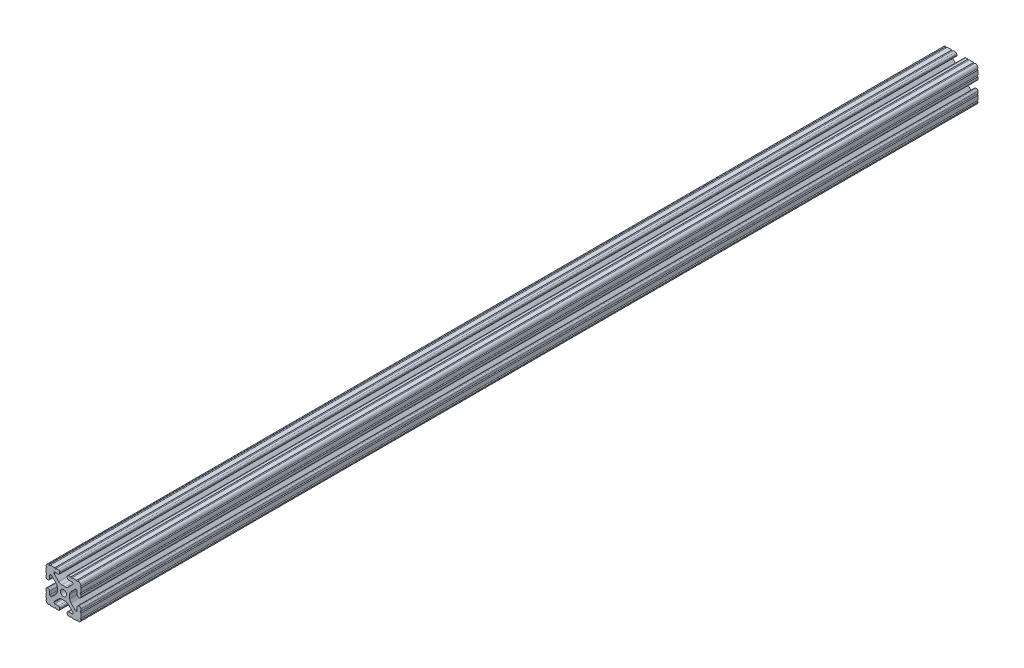
SolidWorks part; units mm, degrees
material "6061 Alloy"
ref_plane "Front Plane" through (0, 0, 0) normal (0, 0, 1) x (1, 0, 0)
ref_plane "Top Plane" through (0, 0, 0) normal (0, 1, 0) x (1, 0, 0)
ref_plane "Right Plane" through (0, 0, 0) normal (1, 0, 0) x (0, 0, -1)
sketch "Sketch1" plane through (0, 0, 0) normal (0, 0, 1) x (1, 0, 0)
  line L0 (0, 25.6181) -> (0, -24.623) construction
  line L1 (-20.8943, 0) -> (20.4607, 0) construction
  line L2 (-10.0229, 12.9148) -> (-5.2522, 8.144)
  line L3 (-10.287, 14.0843) -> (-10.287, 13.5524)
  line L4 (-5.6176, 14.986) -> (-9.3853, 14.986)
  line L5 (-4.064, 17.4964) -> (-4.064, 16.5396)
  line L6 (-7.9742, 19.05) -> (-5.6176, 19.05)
  line L7 (-14.3277, 19.05) -> (-9.4982, 19.05)
  line L8 (-19.05, 9.4961) -> (-19.05, 14.3277)
  line L9 (-19.05, 5.6176) -> (-19.05, 7.9763)
  line L10 (-16.5396, 4.064) -> (-17.4964, 4.064)
  line L11 (-14.986, 9.3853) -> (-14.986, 5.6176)
  line L12 (-13.516, 10.287) -> (-14.0843, 10.287)
  line L13 (-8.1476, 5.2921) -> (-12.8784, 10.0229)
  line L14 (-6.7564, -1.9335) -> (-6.7564, 1.9335)
  line L15 (-12.8784, -10.0229) -> (-8.1476, -5.2921)
  line L16 (-14.0843, -10.287) -> (-13.516, -10.287)
  line L17 (-14.986, -5.6176) -> (-14.986, -9.3853)
  line L18 (-17.4964, -4.064) -> (-16.5396, -4.064)
  line L19 (-19.05, -7.9763) -> (-19.05, -5.6176)
  line L20 (-19.05, -14.3277) -> (-19.05, -9.4961)
  line L21 (-9.4961, -19.05) -> (-14.3277, -19.05)
  line L22 (-5.6176, -19.05) -> (-7.9763, -19.05)
  line L23 (-4.064, -17.4964) -> (-4.064, -16.5396)
  line L24 (10.0229, -12.9148) -> (5.2522, -8.144)
  line L25 (10.287, -14.0843) -> (10.287, -13.5524)
  line L26 (5.6176, -14.986) -> (9.3853, -14.986)
  line L28 (-1.9022, 6.7564) -> (1.9022, 6.7564)
  line L29 (-1.9022, -6.7564) -> (1.9022, -6.7564)
  line L31 (-5.6176, -14.986) -> (-9.3853, -14.986)
  line L32 (-10.287, -14.0843) -> (-10.287, -13.5524)
  line L33 (-10.0229, -12.9148) -> (-5.2522, -8.144)
  line L66 (4.064, -16.5396) -> (4.064, -17.4964)
  line L67 (5.6176, -19.05) -> (7.9763, -19.05)
  line L68 (9.4961, -19.05) -> (14.3277, -19.05)
  line L69 (19.05, -14.3277) -> (19.05, -9.4961)
  line L70 (19.05, -7.9763) -> (19.05, -5.6176)
  line L71 (17.4964, -4.064) -> (16.5396, -4.064)
  line L72 (14.986, -5.6176) -> (14.986, -9.3853)
  line L73 (14.0843, -10.287) -> (13.516, -10.287)
  line L74 (12.8784, -10.0229) -> (8.1476, -5.2921)
  line L75 (6.7564, -1.9335) -> (6.7564, 1.9335)
  line L76 (8.1476, 5.2921) -> (12.8784, 10.0229)
  line L77 (13.516, 10.287) -> (14.0843, 10.287)
  line L78 (14.986, 9.3853) -> (14.986, 5.6176)
  line L79 (16.5396, 4.064) -> (17.4964, 4.064)
  line L80 (19.05, 5.6176) -> (19.05, 7.9763)
  line L81 (19.05, 9.4961) -> (19.05, 14.3277)
  line L82 (14.3277, 19.05) -> (9.4982, 19.05)
  line L83 (7.9742, 19.05) -> (5.6176, 19.05)
  line L84 (4.064, 17.4964) -> (4.064, 16.5396)
  line L85 (5.6176, 14.986) -> (9.3853, 14.986)
  line L86 (10.287, 14.0843) -> (10.287, 13.5524)
  line L87 (10.0229, 12.9148) -> (5.2522, 8.144)
  arc A0 (-10.0229, 12.9148) -> (-10.287, 13.5524) centre (-9.3853, 13.5524) cw
  circle A1 centre (0, 0) radius 3.3274
  arc A2 (-10.287, 14.0843) -> (-9.3853, 14.986) centre (-9.3853, 14.0843) cw
  arc A3 (-4.064, 16.5396) -> (-5.6176, 14.986) centre (-5.6176, 16.5396) cw
  arc A4 (-5.6176, 19.05) -> (-4.064, 17.4964) centre (-5.6176, 17.4964) cw
  arc A5 (-7.9742, 19.05) -> (-9.4982, 19.05) centre (-8.7362, 19.05) cw
  arc A6 (-14.3277, 19.05) -> (-15.8475, 19.05) centre (-15.0876, 18.9933) cw
  arc A7 (-19.05, 15.8475) -> (-15.8475, 19.05) centre (-15.8751, 15.8751) cw
  arc A8 (-19.05, 15.8475) -> (-19.05, 14.3277) centre (-18.9933, 15.0876) cw
  arc A9 (-19.05, 9.4961) -> (-19.05, 7.9763) centre (-18.9933, 8.7362) cw
  arc A10 (-17.4964, 4.064) -> (-19.05, 5.6176) centre (-17.4964, 5.6176) cw
  arc A11 (-14.986, 5.6176) -> (-16.5396, 4.064) centre (-16.5396, 5.6176) cw
  arc A12 (-14.986, 9.3853) -> (-14.0843, 10.287) centre (-14.0843, 9.3853) cw
  arc A13 (-13.516, 10.287) -> (-12.8784, 10.0229) centre (-13.516, 9.3853) cw
  arc A14 (-8.1476, 5.2921) -> (-6.7564, 1.9335) centre (-11.5062, 1.9335) cw
  arc A15 (-6.7564, -1.9335) -> (-8.1476, -5.2921) centre (-11.5062, -1.9335) cw
  arc A16 (-12.8784, -10.0229) -> (-13.516, -10.287) centre (-13.516, -9.3853) cw
  arc A17 (-14.0843, -10.287) -> (-14.986, -9.3853) centre (-14.0843, -9.3853) cw
  arc A18 (-16.5396, -4.064) -> (-14.986, -5.6176) centre (-16.5396, -5.6176) cw
  arc A19 (-19.05, -5.6176) -> (-17.4964, -4.064) centre (-17.4964, -5.6176) cw
  arc A20 (-19.05, -7.9763) -> (-19.05, -9.4961) centre (-18.9933, -8.7362) cw
  arc A21 (-19.05, -14.3277) -> (-19.05, -15.8475) centre (-18.9933, -15.0876) cw
  arc A22 (-15.8475, -19.05) -> (-19.05, -15.8475) centre (-15.8751, -15.8751) cw
  arc A23 (-15.8475, -19.05) -> (-14.3277, -19.05) centre (-15.0876, -18.9933) cw
  arc A24 (-9.4961, -19.05) -> (-7.9763, -19.05) centre (-8.7362, -18.9933) cw
  arc A25 (-4.064, -17.4964) -> (-5.6176, -19.05) centre (-5.6176, -17.4964) cw
  arc A26 (-5.2522, -8.144) -> (-1.9022, -6.7564) centre (-1.9022, -11.494) cw
  arc A27 (1.9022, -6.7564) -> (5.2522, -8.144) centre (1.9022, -11.494) cw
  arc A28 (10.0229, -12.9148) -> (10.287, -13.5524) centre (9.3853, -13.5524) cw
  arc A29 (10.287, -14.0843) -> (9.3853, -14.986) centre (9.3853, -14.0843) cw
  arc A30 (4.064, -16.5396) -> (5.6176, -14.986) centre (5.6176, -16.5396) cw
  arc A31 (-4.064, -16.5396) -> (-5.6176, -14.986) centre (-5.6176, -16.5396) ccw
  arc A32 (-10.287, -14.0843) -> (-9.3853, -14.986) centre (-9.3853, -14.0843) ccw
  arc A33 (-10.0229, -12.9148) -> (-10.287, -13.5524) centre (-9.3853, -13.5524) ccw
  arc A79 (4.064, -17.4964) -> (5.6176, -19.05) centre (5.6176, -17.4964) ccw
  arc A80 (9.4961, -19.05) -> (7.9763, -19.05) centre (8.7362, -18.9933) ccw
  arc A81 (15.8475, -19.05) -> (14.3277, -19.05) centre (15.0876, -18.9933) ccw
  arc A82 (15.8475, -19.05) -> (19.05, -15.8475) centre (15.8751, -15.8751) ccw
  arc A83 (19.05, -14.3277) -> (19.05, -15.8475) centre (18.9933, -15.0876) ccw
  arc A84 (19.05, -7.9763) -> (19.05, -9.4961) centre (18.9933, -8.7362) ccw
  arc A85 (19.05, -5.6176) -> (17.4964, -4.064) centre (17.4964, -5.6176) ccw
  arc A86 (16.5396, -4.064) -> (14.986, -5.6176) centre (16.5396, -5.6176) ccw
  arc A87 (14.0843, -10.287) -> (14.986, -9.3853) centre (14.0843, -9.3853) ccw
  arc A88 (12.8784, -10.0229) -> (13.516, -10.287) centre (13.516, -9.3853) ccw
  arc A89 (6.7564, -1.9335) -> (8.1476, -5.2921) centre (11.5062, -1.9335) ccw
  arc A90 (8.1476, 5.2921) -> (6.7564, 1.9335) centre (11.5062, 1.9335) ccw
  arc A91 (13.516, 10.287) -> (12.8784, 10.0229) centre (13.516, 9.3853) ccw
  arc A92 (14.986, 9.3853) -> (14.0843, 10.287) centre (14.0843, 9.3853) ccw
  arc A93 (14.986, 5.6176) -> (16.5396, 4.064) centre (16.5396, 5.6176) ccw
  arc A94 (17.4964, 4.064) -> (19.05, 5.6176) centre (17.4964, 5.6176) ccw
  arc A95 (19.05, 9.4961) -> (19.05, 7.9763) centre (18.9933, 8.7362) ccw
  arc A96 (19.05, 15.8475) -> (19.05, 14.3277) centre (18.9933, 15.0876) ccw
  arc A97 (19.05, 15.8475) -> (15.8475, 19.05) centre (15.8751, 15.8751) ccw
  arc A98 (14.3277, 19.05) -> (15.8475, 19.05) centre (15.0876, 18.9933) ccw
  arc A99 (7.9742, 19.05) -> (9.4982, 19.05) centre (8.7362, 19.05) ccw
  arc A100 (5.6176, 19.05) -> (4.064, 17.4964) centre (5.6176, 17.4964) ccw
  arc A101 (4.064, 16.5396) -> (5.6176, 14.986) centre (5.6176, 16.5396) ccw
  arc A102 (10.287, 14.0843) -> (9.3853, 14.986) centre (9.3853, 14.0843) ccw
  arc A103 (10.0229, 12.9148) -> (10.287, 13.5524) centre (9.3853, 13.5524) ccw
  arc A104 (1.9022, 6.7564) -> (5.2522, 8.144) centre (1.9022, 11.494) ccw
  arc A105 (-5.2522, 8.144) -> (-1.9022, 6.7564) centre (-1.9022, 11.494) ccw
  dimension "D1" = 6.6548
  dimension "D2" = 19.05
  dimension "D3" = 38.1
  dimension "D4" = 20.574
  dimension "D5" = 13.5128
  dimension "D6" = 4.064
  dimension "D7" = 8.128
  dimension "D8" = 4.064
  dimension "D9" = 12.2936
extrude "Extrude1" add sketch "Sketch1" against normal blind 977.9
